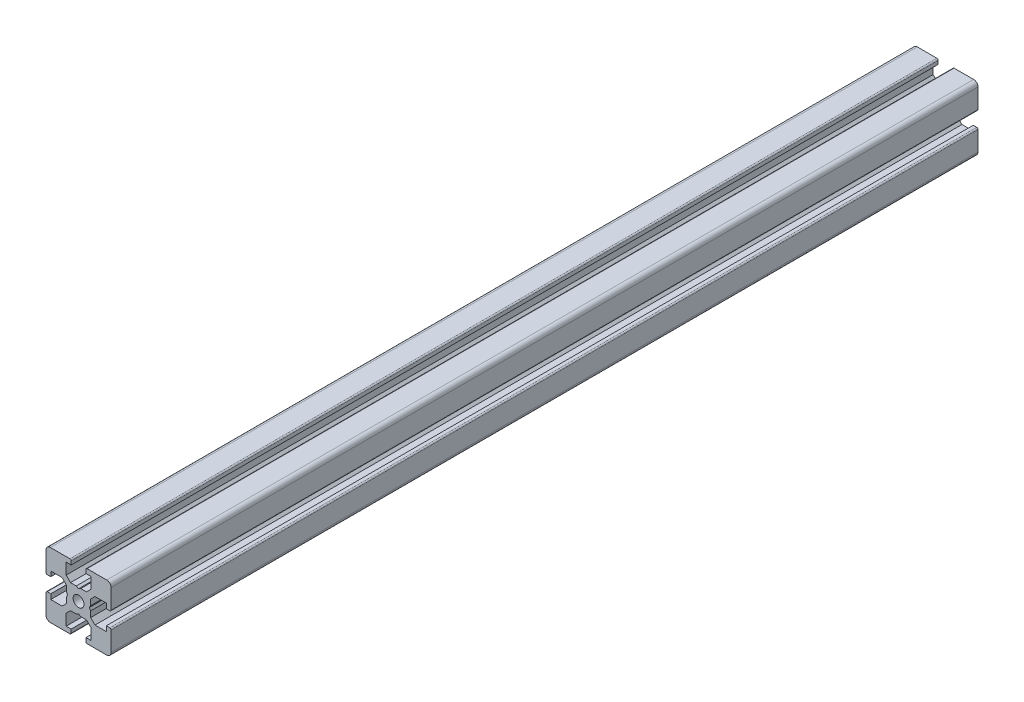
SolidWorks part; units mm, degrees
ref_plane "Front" through (0, 0, 0) normal (0, 0, 1) x (1, 0, 0)
ref_plane "Top" through (0, 0, 0) normal (0, 1, 0) x (1, 0, 0)
ref_plane "Right" through (0, 0, 0) normal (1, 0, 0) x (0, 0, -1)
ref_plane "Plane1" through (0, 0, 300) normal (0, 0, 1) x (1, 0, 0)
sketch "Sketch1" plane through (0, 0, 300) normal (0, 0, 1) x (1, 0, 0)
  line L0 (-7.5, 6.5) -> (-7.5, 2)
  line L1 (-7.2, 1.7) -> (-6.4, 1.7)
  line L2 (-6.4, 1.7) -> (-6.4, 2.85)
  line L3 (-6.4, 2.85) -> (-3.8, 2.85)
  line L4 (-3.8, 2.85) -> (-2.8, 1.85)
  line L5 (-2.8, 1.85) -> (-2.8, 0.5196)
  line L6 (-2.8, 0.5196) -> (-2.5, 0)
  line L7 (-2.5, 0) -> (-2.8, -0.5196)
  line L8 (-2.8, -0.5196) -> (-2.8, -1.85)
  line L9 (-2.8, -1.85) -> (-3.8, -2.85)
  line L10 (-3.8, -2.85) -> (-6.4, -2.85)
  line L11 (-6.4, -2.85) -> (-6.4, -1.7)
  line L12 (-6.4, -1.7) -> (-7.2, -1.7)
  line L13 (-7.5, -2) -> (-7.5, -6.5)
  line L14 (-6.5, -7.5) -> (-2, -7.5)
  line L15 (-1.7, -7.2) -> (-1.7, -6.4)
  line L16 (-1.7, -6.4) -> (-2.85, -6.4)
  line L17 (-2.85, -6.4) -> (-2.85, -3.8)
  line L18 (-2.85, -3.8) -> (-1.85, -2.8)
  line L19 (-1.85, -2.8) -> (-0.5196, -2.8)
  line L20 (-0.5196, -2.8) -> (0, -2.5)
  line L21 (0, -2.5) -> (0.5196, -2.8)
  line L22 (0.5196, -2.8) -> (1.85, -2.8)
  line L23 (1.85, -2.8) -> (2.85, -3.8)
  line L24 (2.85, -3.8) -> (2.85, -6.4)
  line L25 (2.85, -6.4) -> (1.7, -6.4)
  line L26 (1.7, -6.4) -> (1.7, -7.2)
  line L27 (2, -7.5) -> (6.5, -7.5)
  line L28 (7.5, -6.5) -> (7.5, -2)
  line L29 (7.2, -1.7) -> (6.4, -1.7)
  line L30 (6.4, -1.7) -> (6.4, -2.85)
  line L31 (6.4, -2.85) -> (3.8, -2.85)
  line L32 (3.8, -2.85) -> (2.8, -1.85)
  line L33 (2.8, -1.85) -> (2.8, -0.5196)
  line L34 (2.8, -0.5196) -> (2.5, 0)
  line L35 (2.5, 0) -> (2.8, 0.5196)
  line L36 (2.8, 0.5196) -> (2.8, 1.85)
  line L37 (2.8, 1.85) -> (3.8, 2.85)
  line L38 (3.8, 2.85) -> (6.4, 2.85)
  line L39 (6.4, 2.85) -> (6.4, 1.7)
  line L40 (6.4, 1.7) -> (7.2, 1.7)
  line L41 (7.5, 2) -> (7.5, 6.5)
  line L42 (6.5, 7.5) -> (2, 7.5)
  line L43 (1.7, 7.2) -> (1.7, 6.4)
  line L44 (1.7, 6.4) -> (2.85, 6.4)
  line L45 (2.85, 6.4) -> (2.85, 3.8)
  line L46 (2.85, 3.8) -> (1.85, 2.8)
  line L47 (1.85, 2.8) -> (0.5196, 2.8)
  line L48 (0.5196, 2.8) -> (0, 2.5)
  line L49 (0, 2.5) -> (-0.5196, 2.8)
  line L50 (-0.5196, 2.8) -> (-1.85, 2.8)
  line L51 (-1.85, 2.8) -> (-2.85, 3.8)
  line L52 (-2.85, 3.8) -> (-2.85, 6.4)
  line L53 (-2.85, 6.4) -> (-1.7, 6.4)
  line L54 (-1.7, 6.4) -> (-1.7, 7.2)
  line L55 (-2, 7.5) -> (-6.5, 7.5)
  circle A0 centre (0, 0) radius 1.25
  arc A1 (-7.5, 2) -> (-7.2, 1.7) centre (-7.2, 2) ccw
  arc A2 (-7.2, -1.7) -> (-7.5, -2) centre (-7.2, -2) ccw
  arc A3 (-7.5, -6.5) -> (-6.5, -7.5) centre (-6.5, -6.5) ccw
  arc A4 (-2, -7.5) -> (-1.7, -7.2) centre (-2, -7.2) ccw
  arc A5 (1.7, -7.2) -> (2, -7.5) centre (2, -7.2) ccw
  arc A6 (6.5, -7.5) -> (7.5, -6.5) centre (6.5, -6.5) ccw
  arc A7 (7.5, -2) -> (7.2, -1.7) centre (7.2, -2) ccw
  arc A8 (7.2, 1.7) -> (7.5, 2) centre (7.2, 2) ccw
  arc A9 (7.5, 6.5) -> (6.5, 7.5) centre (6.5, 6.5) ccw
  arc A10 (2, 7.5) -> (1.7, 7.2) centre (2, 7.2) ccw
  arc A11 (-1.7, 7.2) -> (-2, 7.5) centre (-2, 7.2) ccw
  arc A12 (-6.5, 7.5) -> (-7.5, 6.5) centre (-6.5, 6.5) ccw
extrude "Boss-Extrude1" add sketch "Sketch1" against normal blind 200
